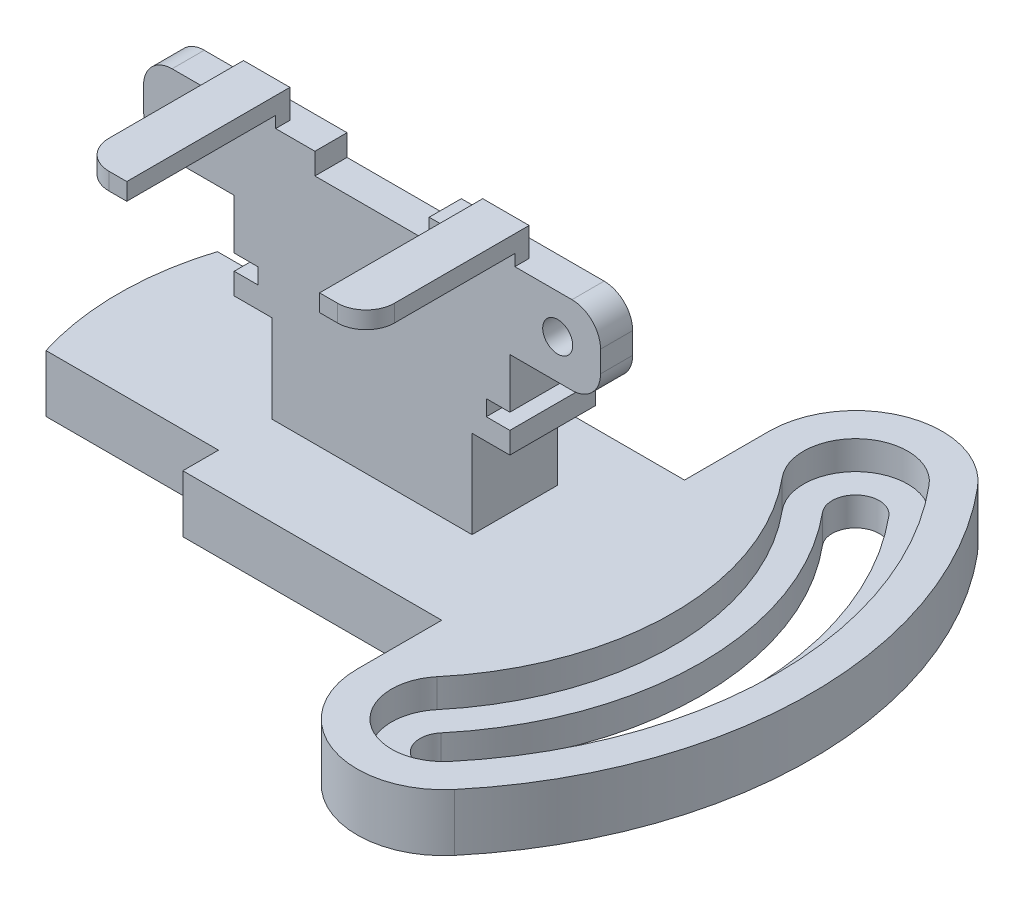
SolidWorks part; units mm, degrees
ref_plane "Front" through (0, 0, 0) normal (0, 0, 1) x (1, 0, 0)
ref_plane "Top" through (0, 0, 0) normal (0, 1, 0) x (1, 0, 0)
ref_plane "Right" through (0, 0, 0) normal (1, 0, 0) x (0, 0, -1)
sketch "Sketch1" plane through (0, 0, 0) normal (0, 0, 1) x (1, 0, 0)
  line L0 (-7, -8.85) -> (-7, -15)
  line L1 (-14, -2.75) -> (-9.65, -2.75)
  line L2 (-16, -0.75) -> (-16, 0.75)
  line L3 (-14, 2.75) -> (-4, 2.75)
  line L4 (16, -0.75) -> (16, 0.75)
  line L5 (-16, -2.75) -> (16, 2.75) construction
  line L6 (-16, 2.75) -> (16, -2.75) construction
  line L7 (-7, -15) -> (7, -15)
  line L8 (7, -15) -> (7, -8.85)
  line L9 (0, 10.3971) -> (0, -15.8755) construction
  line L10 (9.65, -2.75) -> (14, -2.75)
  line L11 (9.65, -2.75) -> (9.65, -6.25)
  line L12 (9.65, -6.25) -> (8, -6.25)
  line L13 (8, -6.25) -> (8, -7.35)
  line L14 (8, -7.35) -> (9.65, -7.35)
  line L15 (9.65, -7.35) -> (9.65, -8.85)
  line L16 (9.65, -8.85) -> (7, -8.85)
  line L17 (-9.65, -2.75) -> (-9.65, -6.25)
  line L18 (-9.65, -6.25) -> (-8, -6.25)
  line L19 (-8, -6.25) -> (-8, -7.35)
  line L20 (-8, -7.35) -> (-9.65, -7.35)
  line L21 (-9.65, -7.35) -> (-9.65, -8.85)
  line L22 (-9.65, -8.85) -> (-7, -8.85)
  line L23 (4, 2.75) -> (4, 1.25)
  line L24 (4, 1.25) -> (-4, 1.25)
  line L25 (-4, 2.75) -> (-4, 1.25)
  line L26 (4, 2.75) -> (14, 2.75)
  arc A0 (14, 2.75) -> (16, 0.75) centre (14, 0.75) cw
  arc A1 (14, -2.75) -> (16, -0.75) centre (14, -0.75) ccw
  arc A2 (-14, -2.75) -> (-16, -0.75) centre (-14, -0.75) cw
  arc A3 (-16, 0.75) -> (-14, 2.75) centre (-14, 0.75) cw
  point P0 (0, 0)
  point P26 (8, -2.75)
  point P31 (7, -15)
  point P34 (-7, -15)
  point P43 (0, 1.25)
  dimension "D3" = 2
  dimension "D7" = 19.3
  dimension "D1" = 32
  dimension "D2" = 5.5
  dimension "D4" = 15
  dimension "D5" = 8
  dimension "D6" = 14
  dimension "D8" = 3.5
  dimension "D9" = 1.1
  dimension "D10" = 1.65
  dimension "D11" = 1.5
  dimension "D12" = 1.5
extrude "Boss-Extrude1" add sketch "Sketch1" along normal mid plane 2.25
sketch "Sketch2" plane through (0, 0, 0) normal (0, 0, 1) x (1, 0, 0)
  line L0 (16, -0.75) -> (16, 0.75) construction
  point P0 (-13, 0)
  point P1 (13, 0)
  point P6 (16, 0)
  dimension "D1" = 26
  dimension "D2" = 13
hole_wizard "M1.8 Clearance Hole1" positions "Sketch5" profile "Sketch6" hole size "M1.8" standard "GB" end condition through all
sketch "Sketch5" plane through (0, 0, 1.125) normal (0, 0, 1) x (1, 0, 0)
  point P0 (-13, 0)
  point P3 (13, 0)
sketch "Sketch6" plane through (-13, 0, 1.125) normal (1, 0, 0) x (0, -1, 0)
  line L0 (0, 0) -> (0, 2.25)
  line L1 (0, 2.25) -> (1.05, 2.25)
  line L2 (1.05, 2.25) -> (1.05, 0)
  line L5 (1.05, 0) -> (0, 0)
  line L11 (0, -6.35) -> (0, 107.95) construction
  dimension "Thru Hole Dia." = 2.1
  dimension "Thru Hole Depth" = 2.25
sketch "Sketch7" plane through (0, -15, 0) normal (0, -1, 0) x (1, 0, 0)
  line L0 (0, -1.125) -> (0, 16.5251) construction
  line L1 (-7, -1.125) -> (7, -1.125) construction
  line L2 (-16.881, 1.125) -> (16.881, 1.125) construction
  line L4 (0, -1.125) -> (-13.4883, 22.2373) construction
  line L5 (-7, -1.125) -> (-7, 6.375)
  line L6 (-7, 6.375) -> (-12.5, 6.375)
  line L7 (-12.5, 6.375) -> (-12.5, 15.875)
  line L8 (-9.5, 18.875) -> (9.5, 18.875)
  line L9 (12.5, 15.875) -> (12.5, 6.375)
  line L10 (12.5, 6.375) -> (7, 6.375)
  line L11 (7, 6.375) -> (7, -1.125)
  line L12 (7, -1.125) -> (-7, -1.125)
  line L13 (-7, 1.125) -> (7, 1.125) construction
  circle A0 centre (0, 1.125) radius 15 construction
  arc A1 (7.7032, 12.2173) -> (-7.7032, 12.2173) centre (0, 1.125) ccw
  arc A2 (9.2032, 14.8153) -> (-9.2032, 14.8153) centre (0, 1.125) ccw
  arc A3 (-9.2032, 14.8153) -> (-7.7032, 12.2173) centre (-8.4532, 13.5163) ccw
  arc A4 (9.2032, 14.8153) -> (7.7032, 12.2173) centre (8.4532, 13.5163) cw
  arc A5 (9.5, 18.875) -> (12.5, 15.875) centre (9.5, 15.875) cw
  arc A6 (-12.5, 15.875) -> (-9.5, 18.875) centre (-9.5, 15.875) cw
  point P23 (0, 18.875)
  point P24 (0, 14.6297)
  point P25 (0, 14.6297)
  point P33 (12.5, 18.875)
  point P36 (-12.5, 18.875)
  dimension "D1" = 30
  dimension "D2" = 1.5
  dimension "D7" = 3
  dimension "D3" = 30
  dimension "D4" = 7.5
  dimension "D5" = 20
  dimension "D6" = 25
extrude "Boss-Extrude2" [suppressed] add sketch "Sketch7" along normal blind 4
fillet "Fillet1" [suppressed] radius 5
sketch "Sketch18" [suppressed] plane through (0, 0, 1.125) normal (0, 0, 1) x (1, 0, 0)
  line L0 (0, 2.75) -> (0, -15) construction
  line L1 (14, 2.75) -> (-14, 2.75) construction
  line L3 (-8, -15) -> (8, -15) construction
sketch "Sketch8" plane through (0, -15, 0) normal (0, -1, 0) x (1, 0, 0)
  line L0 (0, -1.125) -> (53.076, -1.125) construction
  line L1 (0, -1.125) -> (41.7242, 33.8857) construction
  line L2 (0, -1.125) -> (-46.9941, 54.8804) construction
  line L3 (-7, -7.125) -> (-7, -9.625)
  line L4 (-7, -9.625) -> (11.129, -9.625)
  line L5 (0, -1.125) -> (0, 29.9552) construction
  line L6 (11.129, -15.5488) -> (11.129, -9.625)
  line L7 (11.129, 13.2988) -> (11.129, 7.375)
  line L8 (-7, -7.125) -> (-19.0788, -7.125)
  line L10 (-7, 4.875) -> (-7, 7.375)
  line L11 (-7, 7.375) -> (11.129, 7.375)
  line L12 (-7, 4.875) -> (-19.0788, 4.875)
  line L13 (-7, -1.125) -> (7, -1.125) construction
  arc A1 (21.8323, -19.4444) -> (21.8323, 17.1944) centre (0, -1.125) ccw
  circle A2 centre (0, -1.125) radius 22.5 construction
  arc A3 (21.8323, 17.1944) -> (11.129, 13.2988) centre (17.1896, 13.2988) ccw
  arc A4 (11.129, -15.5488) -> (21.8323, -19.4444) centre (17.1896, -15.5488) ccw
  arc A5 (15.9256, -14.4882) -> (15.9256, 12.2382) centre (0, -1.125) ccw
  arc A6 (18.4536, -16.6094) -> (18.4536, 14.3594) centre (0, -1.125) ccw
  arc A11 (18.4536, -16.6094) -> (15.9256, -14.4882) centre (17.1896, -15.5488) cw
  arc A12 (15.9256, 12.2382) -> (18.4536, 14.3594) centre (17.1896, 13.2988) cw
  arc A14 (-19.0788, 4.875) -> (-19.0788, -7.125) centre (0, -1.125) ccw
  point P1 (16.129, -16.8128)
  point P27 (0, -1.125)
  dimension "D1" = 3.3
  dimension "D2" = 45
  dimension "D3" = 6
  dimension "D4" = 6
  dimension "D7" = 40
  dimension "D8" = 20
  dimension "D5" = 40
  dimension "D9" = 2.5
extrude "Boss-Extrude3" add sketch "Sketch8" along normal blind 4
sketch "Sketch10" plane through (0, -19, 0) normal (0, -1, 0) x (-1, 0, 0)
  line L0 (0, 9.625) -> (0, -7.375) construction
  line L1 (7, 9.625) -> (-11.129, 9.625) construction
  line L2 (-11.129, -7.375) -> (7, -7.375) construction
  circle A0 centre (0, 1.125) radius 4
  dimension "D1" = 8
extrude "Boss-Extrude4" add sketch "Sketch10" along normal blind 2.8
sketch "Sketch11" plane through (0, -15, 0) normal (0, 1, 0) x (1, 0, 0)
  arc A4 (18.4536, 16.6094) -> (15.9256, 14.4882) centre (17.1896, 15.5488) ccw construction
  arc A5 (15.9256, -12.2382) -> (15.9256, 14.4882) centre (0, 1.125) ccw construction
  arc A6 (15.9256, -12.2382) -> (18.4536, -14.3594) centre (17.1896, -13.2988) ccw construction
  arc A7 (18.4536, -14.3594) -> (18.4536, 16.6094) centre (0, 1.125) ccw construction
  arc A8 (18.4536, 16.6094) -> (15.9256, 14.4882) centre (17.1896, 15.5488) ccw
  arc A9 (15.9256, -12.2382) -> (15.9256, 14.4882) centre (0, 1.125) ccw
  arc A10 (15.9256, -12.2382) -> (18.4536, -14.3594) centre (17.1896, -13.2988) ccw
  arc A11 (18.4536, -14.3594) -> (18.4536, 16.6094) centre (0, 1.125) ccw
  arc A12 (14.3935, -10.9526) -> (14.3935, 13.2026) centre (0, 1.125) ccw
  arc A13 (19.9857, 17.895) -> (14.3935, 13.2026) centre (17.1896, 15.5488) ccw
  arc A14 (19.9857, -15.645) -> (19.9857, 17.895) centre (0, 1.125) ccw
  arc A15 (14.3935, -10.9526) -> (19.9857, -15.645) centre (17.1896, -13.2988) ccw
  dimension "D1" = 2
extrude "Cut-Extrude1" cut sketch "Sketch11" against normal blind 2
sketch "Sketch13" plane through (0, 2.75, 0) normal (0, 1, 0) x (1, 0, 0)
  line L0 (-7, 1.125) -> (-7, 18.5103)
  line L1 (-4, 1.125) -> (-14, 1.125) construction
  line L2 (7, 1.125) -> (7, 8.2137)
  line L3 (-7, 1.125) -> (7, 1.125)
  line L4 (-11, -1.125) -> (11, -1.125)
  line L5 (-4, -1.125) -> (-14, -1.125) construction
  line L6 (-7, -16.2603) -> (-7, -5.125)
  line L7 (7, -5.9637) -> (7, -5.125)
  circle A0 centre (-9, 1.125) radius 17.5 construction
  arc A1 (7, 8.2137) -> (-7.9397, 18.5928) centre (-9, 1.125) ccw
  arc A2 (7, -5.9637) -> (-7, -16.2603) centre (-9, 1.125) cw
  arc A3 (-7, -5.125) -> (-11, -1.125) centre (-11, -5.125) ccw
  arc A4 (7, -5.125) -> (11, -1.125) centre (11, -5.125) cw
  point P19 (0, -1.125)
  dimension "D1" = 35
  dimension "D2" = 4
  dimension "D3" = 22
extrude "Boss-Extrude5" [suppressed] add sketch "Sketch13" against normal up to surface (5.5 mm away)
ref_plane "Plane1" through (0, -6, 0) normal (0, 1, 0) x (1, 0, 0)
sketch "Sketch19" plane through (0, 0, 1.125) normal (0, 0, 1) x (1, 0, 0)
  line L0 (0, 2.75) -> (0, -19) construction
  line L1 (-14, 2.75) -> (-4, 2.75) construction
  line L2 (-4, -19) -> (4, -19) construction
  line L5 (-9.65, -2.75) -> (-9.65, -6.25) construction
  line L6 (-9.65, -5) -> (-9.65, -6.25)
  line L7 (-9.65, -6.25) -> (-8, -6.25)
  line L8 (-8, -6.25) -> (-8, -7.35)
  line L9 (-8, -7.35) -> (-9.65, -7.35)
  line L10 (-9.65, -7.35) -> (-9.65, -8.85)
  line L11 (-9.65, -8.85) -> (-6.6, -8.85)
  line L12 (-6.6, -8.85) -> (-6.6, -5)
  line L13 (-6.6, -5) -> (-9.65, -5)
  dimension "D2" = 13.2
  dimension "D4" = 7.75
extrude "Boss-Extrude9" add sketch "Sketch19" against normal blind 6
mirror "Mirror1" about plane through (0, 0, 0) normal (1, 0, 0) of "Boss-Extrude9"
sketch "Sketch20" plane through (-8, 0, 0) normal (-1, 0, 0) x (0, 0, 1)
  line L0 (7.375, -19) -> (7.375, -15) construction
  line L1 (7.375, -1.25) -> (7.7768, -1.25) construction
  line L2 (1.125, 2.75) -> (-1.125, 2.75) construction
  line L3 (7.375, 2.75) -> (1.125, 2.75) construction
  line L4 (1.125, 2.75) -> (7.375, 2.75)
  line L5 (7.375, 2.75) -> (7.375, -1.25)
  spline S0 degree 3 poles (1.125, 2.75) (4.4583, 2.75) (5.7083, -1.25) (7.375, -1.25) knots 0 0 0 0 1 1 1 1
  dimension "D1" = 10
  dimension "D2" = 5
  dimension "D3" = 4
extrude "Cut-Extrude2" [suppressed] cut sketch "Sketch20" against normal up to surface (16 mm away)
sketch "Sketch21" plane through (0, 2.75, 0) normal (0, 1, 0) x (1, 0, 0)
  line L0 (-10, -1.125) -> (-6.75, -1.125)
  line L1 (-4, -1.125) -> (-14, -1.125) construction
  line L2 (-6.75, -1.125) -> (-6.75, -0.125)
  line L3 (-6.75, -0.125) -> (-10, -0.125)
  line L4 (-10, -0.125) -> (-10, -1.125)
  line L5 (0, 4.8371) -> (0, -5.494) construction
  line L8 (10, -0.125) -> (10, -1.125)
  line L9 (6.75, -0.125) -> (10, -0.125)
  line L10 (6.75, -1.125) -> (6.75, -0.125)
  line L11 (10, -1.125) -> (6.75, -1.125)
  dimension "D1" = 13.5
  dimension "D2" = 20
  dimension "D3" = 1
extrude "Boss-Extrude10" add sketch "Sketch21" along normal blind 2
sketch "Sketch24" plane through (0, 0, 1.125) normal (0, 0, 1) x (1, 0, 0)
  line L0 (-4, -4.6947) -> (-4, 4.75) construction
  line L1 (-10, 4.75) -> (-4, 4.75)
  line L2 (-10, 4.75) -> (-10, 3.35)
  line L3 (-10, 3.35) -> (-4, 3.35)
  line L4 (-4, 4.75) -> (-4, 3.35)
  line L6 (10, 4.75) -> (4, 4.75)
  line L7 (10, 4.75) -> (10, 3.35)
  line L8 (10, 3.35) -> (4, 3.35)
  line L9 (4, 4.75) -> (4, 3.35)
  dimension "D1" = 1.4
sketch "Sketch26" plane through (0, 4.75, 0) normal (0, 1, 0) x (1, 0, 0)
  line L0 (-6.75, -0.125) -> (-10, -0.125) construction
  line L1 (-10, -0.125) -> (-6.75, -0.125)
  line L2 (-10, -0.125) -> (-10, -9.5476)
  line L3 (-8, -11.5476) -> (-6.75, -11.5476)
  line L4 (-6.75, -0.125) -> (-6.75, -11.5476)
  line L5 (-10, -0.125) -> (-10, -1.125) construction
  line L6 (-6.75, -1.125) -> (-6.75, -0.125) construction
  line L7 (0, 17.8039) -> (0, -18.1906) construction
  line L8 (6.75, -0.125) -> (6.75, -11.5476)
  line L9 (8, -11.5476) -> (6.75, -11.5476)
  line L10 (10, -0.125) -> (10, -9.5476)
  line L11 (10, -0.125) -> (6.75, -0.125)
  arc A0 (-10, -9.5476) -> (-8, -11.5476) centre (-8, -9.5476) ccw
  arc A1 (10, -9.5476) -> (8, -11.5476) centre (8, -9.5476) cw
  dimension "D1" = 2
extrude "Boss-Extrude13" add sketch "Sketch26" against normal blind 1.2 contours L2 A0 L3 L4 L1 | L10 A1 L9 L8 L11
sketch "Sketch25" plane through (0, -5, 0) normal (0, 1, 0) x (1, 0, 0)
  line L0 (-4, 1.125) -> (-14, 1.125) construction
  line L1 (-7, 1.125) -> (7, 1.125)
  line L2 (-7, 1.125) -> (-7, 4.875)
  line L3 (-7, 4.875) -> (7, 4.875)
  line L4 (7, 1.125) -> (7, 4.875)
  line L6 (6.6, 4.875) -> (9.65, 4.875) construction
  point P7 (0, 1.125)
  point P8 (0, 0)
  point P9 (0, 0)
  dimension "D1" = 14
extrude "Boss-Extrude12" add sketch "Sketch25" against normal up to surface (10 mm away) up to face at (18.6414, -15, -1.125)
